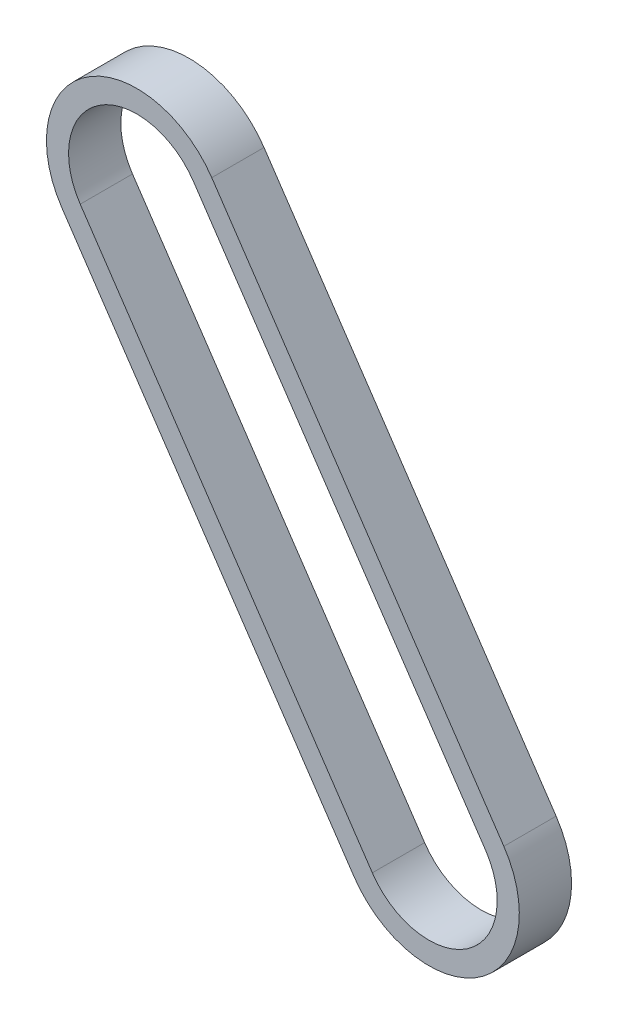
SolidWorks part; units mm, degrees
ref_plane "Front Plane" through (0, 0, 0) normal (0, 0, 1) x (1, 0, 0)
ref_plane "Top Plane" through (0, 0, 0) normal (0, 1, 0) x (1, 0, 0)
ref_plane "Right Plane" through (0, 0, 0) normal (1, 0, 0) x (0, 0, -1)
sketch "Sketch2" plane through (0, 0, 0) normal (0, 0, 1) x (1, 0, 0)
  line L0 (0, 0) -> (1, 0) construction
  line L1 (0, 0) -> (0, 1) construction
  line L2 (11.4682, 7.7354) -> (61.76, -66.8254)
  line L3 (38.8237, -82.2961) -> (-11.4682, -7.7354)
  arc A0 (-11.4682, -7.7354) -> (11.4682, 7.7354) centre (0, 0) cw
  arc A1 (61.76, -66.8254) -> (38.8237, -82.2961) centre (50.2919, -74.5607) cw
extrude "Extrude-Thin1" add sketch "Sketch2" along normal mid plane 9 thin thin type two direction wall 1.73 second wall 2.08
equation "\"D1@Extrude-Thin1\"=9mm"
